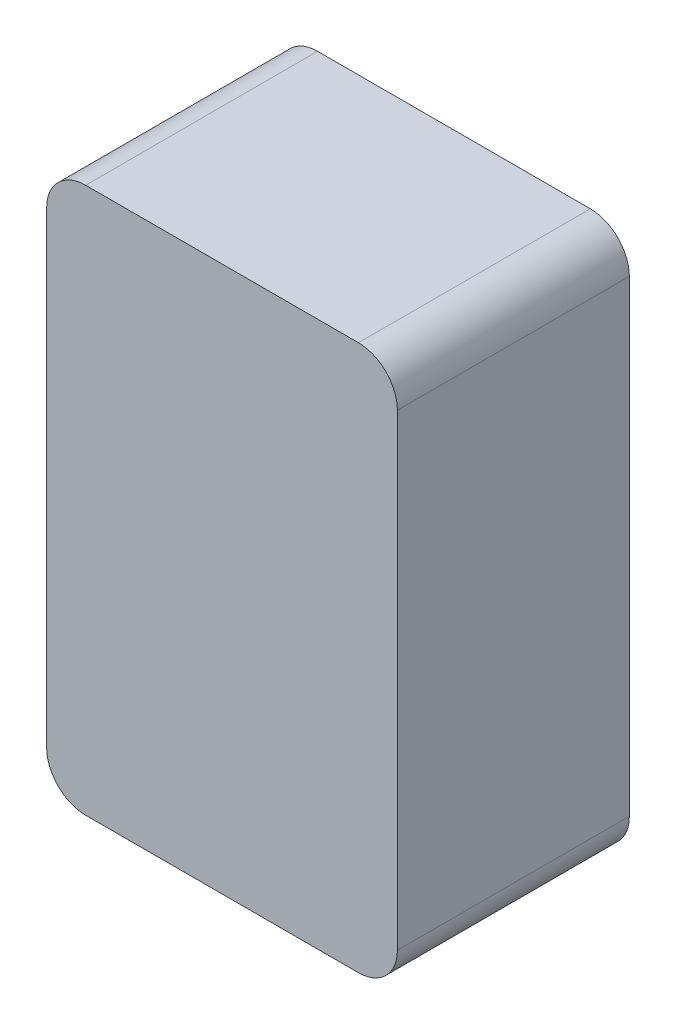
SolidWorks part; units mm, degrees
material "ABS"
ref_plane "X-Y Datum" through (0, 0, 0) normal (0, 0, 1) x (1, 0, 0)
ref_plane "X-Z Datum" through (0, 0, 0) normal (0, 1, 0) x (1, 0, 0)
ref_plane "Y-Z Datum" through (0, 0, 0) normal (1, 0, 0) x (0, 0, -1)
sketch "Sketch1" plane through (0, 0, 0) normal (0, 0, 1) x (1, 0, 0)
  line L1 (-14.2875, 22.225) -> (14.2875, 22.225)
  line L2 (-14.2875, 22.225) -> (-14.2875, -22.225)
  line L3 (-14.2875, -22.225) -> (14.2875, -22.225)
  line L4 (14.2875, 22.225) -> (14.2875, -22.225)
  line L5 (-14.2875, 22.225) -> (14.2875, -22.225) construction
  line L6 (-14.2875, -22.225) -> (14.2875, 22.225) construction
  point P0 (0, 0)
  dimension "D1" = 28.575
  dimension "D2" = 44.45
extrude "Boss-Extrude1" add sketch "Sketch1" along normal blind 18.8976
fillet "Fillet1" radius 3.175 4 edges at (-14.2875, -22.225, 9.4488) (14.2875, -22.225, 9.4488) (-14.2875, 22.225, 9.4488) (14.2875, 22.225, 9.4488)
